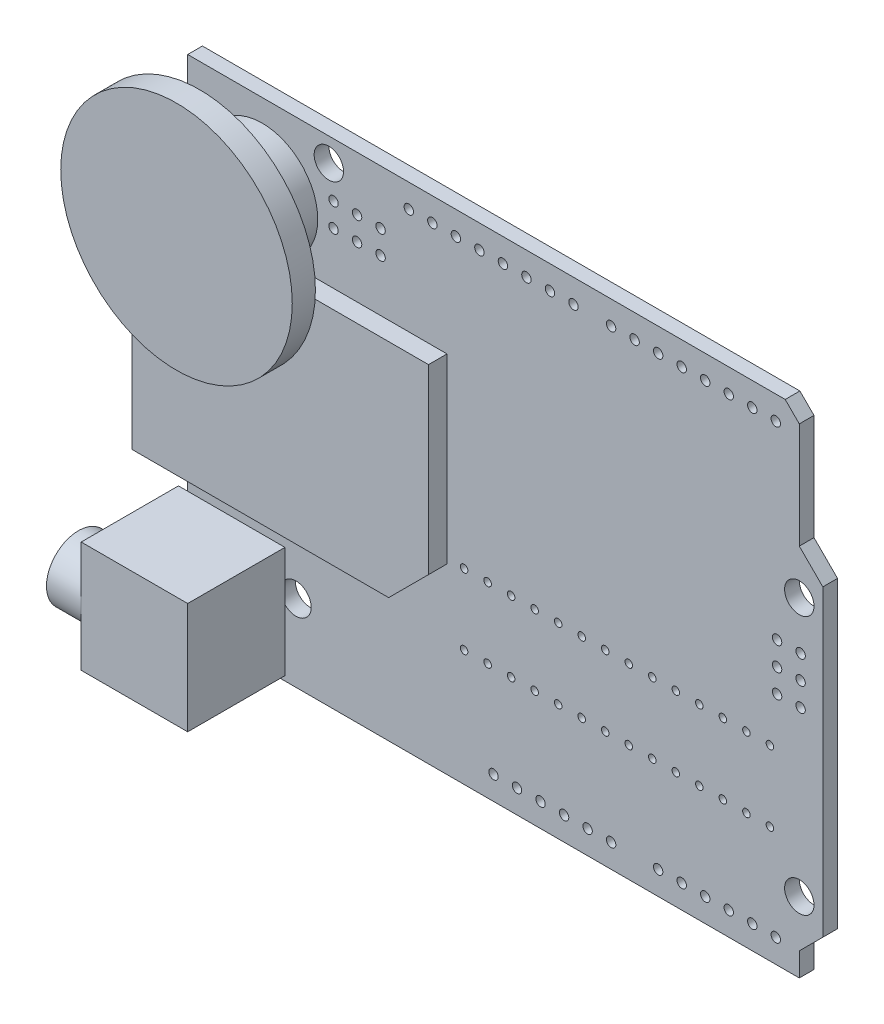
SolidWorks part; units mm, degrees
ref_plane "Front" through (0, 0, 0) normal (0, 0, 1) x (1, 0, 0)
ref_plane "Top" through (0, 0, 0) normal (0, 1, 0) x (1, 0, 0)
ref_plane "Right" through (0, 0, 0) normal (1, 0, 0) x (0, 0, -1)
sketch "Sketch1" plane through (0, 0, 0) normal (0, 0, 1) x (1, 0, 0)
  line L0 (-34.2899, 0) -> (34.2899, 0) construction
  line L1 (0, 0) -> (0, 7.605) construction
  line L2 (31.7499, 13.716) -> (31.7499, 25.146) construction
  line L3 (-34.2899, -26.67) -> (-34.2899, 26.67) construction
  line L4 (-34.2899, -26.67) -> (31.7499, -26.67) construction
  line L5 (31.7499, -26.67) -> (31.7499, -24.13) construction
  line L6 (31.7499, -24.13) -> (34.2899, -21.59) construction
  line L7 (34.2899, -21.59) -> (34.2899, 11.176) construction
  line L8 (31.7499, 13.716) -> (34.2899, 11.176) construction
  line L9 (30.2259, 26.67) -> (31.7499, 25.146) construction
  line L10 (-34.2899, 26.67) -> (30.2259, 26.67) construction
  arc A0 (-21.12, -24.13) -> (-19.5201, -24.13) centre (-20.3201, -24.13) ccw construction
  arc A1 (-19.5201, -24.13) -> (-21.12, -24.13) centre (-20.3201, -24.13) ccw construction
  arc A2 (-19.85, 24.13) -> (-18.2501, 24.13) centre (-19.0501, 24.13) ccw construction
  arc A3 (-18.2501, 24.13) -> (-19.85, 24.13) centre (-19.0501, 24.13) ccw construction
  arc A4 (30.95, -19.05) -> (32.5499, -19.05) centre (31.7499, -19.05) ccw construction
  arc A5 (32.5499, -19.05) -> (30.95, -19.05) centre (31.7499, -19.05) ccw construction
  arc A6 (30.95, 8.89) -> (32.5499, 8.89) centre (31.7499, 8.89) ccw construction
  arc A7 (32.5499, 8.89) -> (30.95, 8.89) centre (31.7499, 8.89) ccw construction
  arc A8 (28.3717, -14.097) -> (28.7781, -14.097) centre (28.5749, -14.097) ccw construction
  arc A9 (28.7781, -14.097) -> (28.3717, -14.097) centre (28.5749, -14.097) ccw construction
  arc A10 (25.8317, -14.097) -> (26.2381, -14.097) centre (26.0349, -14.097) ccw construction
  arc A11 (26.2381, -14.097) -> (25.8317, -14.097) centre (26.0349, -14.097) ccw construction
  arc A12 (23.2917, -14.097) -> (23.6981, -14.097) centre (23.4949, -14.097) ccw construction
  arc A13 (23.6981, -14.097) -> (23.2917, -14.097) centre (23.4949, -14.097) ccw construction
  arc A14 (20.7517, -14.097) -> (21.1581, -14.097) centre (20.9549, -14.097) ccw construction
  arc A15 (21.1581, -14.097) -> (20.7517, -14.097) centre (20.9549, -14.097) ccw construction
  arc A16 (18.2117, -14.097) -> (18.6181, -14.097) centre (18.4149, -14.097) ccw construction
  arc A17 (18.6181, -14.097) -> (18.2117, -14.097) centre (18.4149, -14.097) ccw construction
  arc A18 (15.6717, -14.097) -> (16.0781, -14.097) centre (15.8749, -14.097) ccw construction
  arc A19 (16.0781, -14.097) -> (15.6717, -14.097) centre (15.8749, -14.097) ccw construction
  arc A20 (13.1317, -14.097) -> (13.5381, -14.097) centre (13.3349, -14.097) ccw construction
  arc A21 (13.5381, -14.097) -> (13.1317, -14.097) centre (13.3349, -14.097) ccw construction
  arc A22 (10.5917, -14.097) -> (10.9981, -14.097) centre (10.7949, -14.097) ccw construction
  arc A23 (10.9981, -14.097) -> (10.5917, -14.097) centre (10.7949, -14.097) ccw construction
  arc A24 (8.0517, -14.097) -> (8.4581, -14.097) centre (8.2549, -14.097) ccw construction
  arc A25 (8.4581, -14.097) -> (8.0517, -14.097) centre (8.2549, -14.097) ccw construction
  arc A26 (5.5117, -14.097) -> (5.9181, -14.097) centre (5.7149, -14.097) ccw construction
  arc A27 (5.9181, -14.097) -> (5.5117, -14.097) centre (5.7149, -14.097) ccw construction
  arc A28 (2.9717, -14.097) -> (3.3781, -14.097) centre (3.1749, -14.097) ccw construction
  arc A29 (3.3781, -14.097) -> (2.9717, -14.097) centre (3.1749, -14.097) ccw construction
  arc A30 (0.4317, -14.097) -> (0.8381, -14.097) centre (0.6349, -14.097) ccw construction
  arc A31 (0.8381, -14.097) -> (0.4317, -14.097) centre (0.6349, -14.097) ccw construction
  arc A32 (-2.1083, -14.097) -> (-1.7019, -14.097) centre (-1.9051, -14.097) ccw construction
  arc A33 (-1.7019, -14.097) -> (-2.1083, -14.097) centre (-1.9051, -14.097) ccw construction
  arc A34 (-4.6483, -14.097) -> (-4.2419, -14.097) centre (-4.4451, -14.097) ccw construction
  arc A35 (-4.2419, -14.097) -> (-4.6483, -14.097) centre (-4.4451, -14.097) ccw construction
  arc A36 (-4.6483, -6.477) -> (-4.2419, -6.477) centre (-4.4451, -6.477) ccw construction
  arc A37 (-4.2419, -6.477) -> (-4.6483, -6.477) centre (-4.4451, -6.477) ccw construction
  arc A38 (-2.1083, -6.477) -> (-1.7019, -6.477) centre (-1.9051, -6.477) ccw construction
  arc A39 (-1.7019, -6.477) -> (-2.1083, -6.477) centre (-1.9051, -6.477) ccw construction
  arc A40 (0.4317, -6.477) -> (0.8381, -6.477) centre (0.6349, -6.477) ccw construction
  arc A41 (0.8381, -6.477) -> (0.4317, -6.477) centre (0.6349, -6.477) ccw construction
  arc A42 (2.9717, -6.477) -> (3.3781, -6.477) centre (3.1749, -6.477) ccw construction
  arc A43 (3.3781, -6.477) -> (2.9717, -6.477) centre (3.1749, -6.477) ccw construction
  arc A44 (5.5117, -6.477) -> (5.9181, -6.477) centre (5.7149, -6.477) ccw construction
  arc A45 (5.9181, -6.477) -> (5.5117, -6.477) centre (5.7149, -6.477) ccw construction
  arc A46 (8.0517, -6.477) -> (8.4581, -6.477) centre (8.2549, -6.477) ccw construction
  arc A47 (8.4581, -6.477) -> (8.0517, -6.477) centre (8.2549, -6.477) ccw construction
  arc A48 (10.5917, -6.477) -> (10.9981, -6.477) centre (10.7949, -6.477) ccw construction
  arc A49 (10.9981, -6.477) -> (10.5917, -6.477) centre (10.7949, -6.477) ccw construction
  arc A50 (13.1317, -6.477) -> (13.5381, -6.477) centre (13.3349, -6.477) ccw construction
  arc A51 (13.5381, -6.477) -> (13.1317, -6.477) centre (13.3349, -6.477) ccw construction
  arc A52 (15.6717, -6.477) -> (16.0781, -6.477) centre (15.8749, -6.477) ccw construction
  arc A53 (16.0781, -6.477) -> (15.6717, -6.477) centre (15.8749, -6.477) ccw construction
  arc A54 (18.2117, -6.477) -> (18.6181, -6.477) centre (18.4149, -6.477) ccw construction
  arc A55 (18.6181, -6.477) -> (18.2117, -6.477) centre (18.4149, -6.477) ccw construction
  arc A56 (20.7517, -6.477) -> (21.1581, -6.477) centre (20.9549, -6.477) ccw construction
  arc A57 (21.1581, -6.477) -> (20.7517, -6.477) centre (20.9549, -6.477) ccw construction
  arc A58 (23.2917, -6.477) -> (23.6981, -6.477) centre (23.4949, -6.477) ccw construction
  arc A59 (23.6981, -6.477) -> (23.2917, -6.477) centre (23.4949, -6.477) ccw construction
  arc A60 (25.8317, -6.477) -> (26.2381, -6.477) centre (26.0349, -6.477) ccw construction
  arc A61 (26.2381, -6.477) -> (25.8317, -6.477) centre (26.0349, -6.477) ccw construction
  arc A62 (28.3717, -6.477) -> (28.7781, -6.477) centre (28.5749, -6.477) ccw construction
  arc A63 (28.7781, -6.477) -> (28.3717, -6.477) centre (28.5749, -6.477) ccw construction
  arc A64 (-31.0299, 5.43) -> (-29.93, 5.43) centre (-30.4799, 5.43) ccw construction
  arc A65 (-29.93, 5.43) -> (-31.0299, 5.43) centre (-30.4799, 5.43) ccw construction
  arc A66 (-31.0299, 17.43) -> (-29.93, 17.43) centre (-30.4799, 17.43) ccw construction
  arc A67 (-29.93, 17.43) -> (-31.0299, 17.43) centre (-30.4799, 17.43) ccw construction
  arc A68 (-28.0074, 10.1801) -> (-27.5324, 10.1801) centre (-27.7699, 10.1801) ccw construction
  arc A69 (-27.5324, 10.1801) -> (-28.0074, 10.1801) centre (-27.7699, 10.1801) ccw construction
  arc A70 (-28.0074, 12.6799) -> (-27.5324, 12.6799) centre (-27.7699, 12.6799) ccw construction
  arc A71 (-27.5324, 12.6799) -> (-28.0074, 12.6799) centre (-27.7699, 12.6799) ccw construction
  arc A72 (-26.0075, 12.6799) -> (-25.5325, 12.6799) centre (-25.77, 12.6799) ccw construction
  arc A73 (-25.5325, 12.6799) -> (-26.0075, 12.6799) centre (-25.77, 12.6799) ccw construction
  arc A74 (-26.0075, 10.1801) -> (-25.5325, 10.1801) centre (-25.77, 10.1801) ccw construction
  arc A75 (-25.5325, 10.1801) -> (-26.0075, 10.1801) centre (-25.77, 10.1801) ccw construction
  arc A76 (-29.4258, -18.3642) -> (-27.7748, -18.3642) centre (-28.6003, -18.3642) ccw construction
  arc A77 (-27.7748, -18.3642) -> (-29.4258, -18.3642) centre (-28.6003, -18.3642) ccw construction
  arc A78 (-23.4316, -18.3642) -> (-21.7806, -18.3642) centre (-22.6061, -18.3642) ccw construction
  arc A79 (-21.7806, -18.3642) -> (-23.4316, -18.3642) centre (-22.6061, -18.3642) ccw construction
  arc A80 (-26.4286, -23.368) -> (-24.7776, -23.368) centre (-25.6031, -23.368) ccw construction
  arc A81 (-24.7776, -23.368) -> (-26.4286, -23.368) centre (-25.6031, -23.368) ccw construction
  arc A82 (8.7375, -2.54) -> (9.0423, -2.54) centre (8.8899, -2.54) ccw construction
  arc A83 (9.0423, -2.54) -> (8.7375, -2.54) centre (8.8899, -2.54) ccw construction
  arc A84 (3.6575, -2.54) -> (3.9623, -2.54) centre (3.8099, -2.54) ccw construction
  arc A85 (3.9623, -2.54) -> (3.6575, -2.54) centre (3.8099, -2.54) ccw construction
  arc A86 (-20.4725, 3.81) -> (-20.1677, 3.81) centre (-20.3201, 3.81) ccw construction
  arc A87 (-20.1677, 3.81) -> (-20.4725, 3.81) centre (-20.3201, 3.81) ccw construction
  arc A88 (-15.3925, 3.81) -> (-15.0877, 3.81) centre (-15.2401, 3.81) ccw construction
  arc A89 (-15.0877, 3.81) -> (-15.3925, 3.81) centre (-15.2401, 3.81) ccw construction
  arc A90 (11.1759, -24.13) -> (11.6839, -24.13) centre (11.4299, -24.13) ccw construction
  arc A91 (11.6839, -24.13) -> (11.1759, -24.13) centre (11.4299, -24.13) ccw construction
  arc A92 (8.6359, -24.13) -> (9.1439, -24.13) centre (8.8899, -24.13) ccw construction
  arc A93 (9.1439, -24.13) -> (8.6359, -24.13) centre (8.8899, -24.13) ccw construction
  arc A94 (6.0959, -24.13) -> (6.6039, -24.13) centre (6.3499, -24.13) ccw construction
  arc A95 (6.6039, -24.13) -> (6.0959, -24.13) centre (6.3499, -24.13) ccw construction
  arc A96 (3.5559, -24.13) -> (4.0639, -24.13) centre (3.8099, -24.13) ccw construction
  arc A97 (4.0639, -24.13) -> (3.5559, -24.13) centre (3.8099, -24.13) ccw construction
  arc A98 (1.0159, -24.13) -> (1.5239, -24.13) centre (1.2699, -24.13) ccw construction
  arc A99 (1.5239, -24.13) -> (1.0159, -24.13) centre (1.2699, -24.13) ccw construction
  arc A100 (-1.5241, -24.13) -> (-1.0161, -24.13) centre (-1.2701, -24.13) ccw construction
  arc A101 (-1.0161, -24.13) -> (-1.5241, -24.13) centre (-1.2701, -24.13) ccw construction
  arc A102 (11.1759, 24.13) -> (11.6839, 24.13) centre (11.4299, 24.13) ccw construction
  arc A103 (11.6839, 24.13) -> (11.1759, 24.13) centre (11.4299, 24.13) ccw construction
  arc A104 (13.7159, 24.13) -> (14.2239, 24.13) centre (13.9699, 24.13) ccw construction
  arc A105 (14.2239, 24.13) -> (13.7159, 24.13) centre (13.9699, 24.13) ccw construction
  arc A106 (16.2559, 24.13) -> (16.7639, 24.13) centre (16.5099, 24.13) ccw construction
  arc A107 (16.7639, 24.13) -> (16.2559, 24.13) centre (16.5099, 24.13) ccw construction
  arc A108 (18.7959, 24.13) -> (19.3039, 24.13) centre (19.0499, 24.13) ccw construction
  arc A109 (19.3039, 24.13) -> (18.7959, 24.13) centre (19.0499, 24.13) ccw construction
  arc A110 (21.3359, 24.13) -> (21.8439, 24.13) centre (21.5899, 24.13) ccw construction
  arc A111 (21.8439, 24.13) -> (21.3359, 24.13) centre (21.5899, 24.13) ccw construction
  arc A112 (23.8759, 24.13) -> (24.3839, 24.13) centre (24.1299, 24.13) ccw construction
  arc A113 (24.3839, 24.13) -> (23.8759, 24.13) centre (24.1299, 24.13) ccw construction
  arc A114 (26.4159, 24.13) -> (26.9239, 24.13) centre (26.6699, 24.13) ccw construction
  arc A115 (26.9239, 24.13) -> (26.4159, 24.13) centre (26.6699, 24.13) ccw construction
  arc A116 (28.9559, 24.13) -> (29.4639, 24.13) centre (29.2099, 24.13) ccw construction
  arc A117 (29.4639, 24.13) -> (28.9559, 24.13) centre (29.2099, 24.13) ccw construction
  arc A118 (-10.6681, 24.13) -> (-10.1601, 24.13) centre (-10.4141, 24.13) ccw construction
  arc A119 (-10.1601, 24.13) -> (-10.6681, 24.13) centre (-10.4141, 24.13) ccw construction
  arc A120 (-8.1281, 24.13) -> (-7.6201, 24.13) centre (-7.8741, 24.13) ccw construction
  arc A121 (-7.6201, 24.13) -> (-8.1281, 24.13) centre (-7.8741, 24.13) ccw construction
  arc A122 (-5.5881, 24.13) -> (-5.0801, 24.13) centre (-5.3341, 24.13) ccw construction
  arc A123 (-5.0801, 24.13) -> (-5.5881, 24.13) centre (-5.3341, 24.13) ccw construction
  arc A124 (-3.0481, 24.13) -> (-2.5401, 24.13) centre (-2.7941, 24.13) ccw construction
  arc A125 (-2.5401, 24.13) -> (-3.0481, 24.13) centre (-2.7941, 24.13) ccw construction
  arc A126 (-0.5081, 24.13) -> (-0.0001, 24.13) centre (-0.2541, 24.13) ccw construction
  arc A127 (-0.0001, 24.13) -> (-0.5081, 24.13) centre (-0.2541, 24.13) ccw construction
  arc A128 (2.0319, 24.13) -> (2.5399, 24.13) centre (2.2859, 24.13) ccw construction
  arc A129 (2.5399, 24.13) -> (2.0319, 24.13) centre (2.2859, 24.13) ccw construction
  arc A130 (4.5719, 24.13) -> (5.0799, 24.13) centre (4.8259, 24.13) ccw construction
  arc A131 (5.0799, 24.13) -> (4.5719, 24.13) centre (4.8259, 24.13) ccw construction
  arc A132 (7.1119, 24.13) -> (7.6199, 24.13) centre (7.3659, 24.13) ccw construction
  arc A133 (7.6199, 24.13) -> (7.1119, 24.13) centre (7.3659, 24.13) ccw construction
  arc A134 (-18.7961, 18.288) -> (-18.2881, 18.288) centre (-18.5421, 18.288) ccw construction
  arc A135 (-18.2881, 18.288) -> (-18.7961, 18.288) centre (-18.5421, 18.288) ccw construction
  arc A136 (-18.7961, 20.828) -> (-18.2881, 20.828) centre (-18.5421, 20.828) ccw construction
  arc A137 (-18.2881, 20.828) -> (-18.7961, 20.828) centre (-18.5421, 20.828) ccw construction
  arc A138 (-16.2561, 18.288) -> (-15.7481, 18.288) centre (-16.0021, 18.288) ccw construction
  arc A139 (-15.7481, 18.288) -> (-16.2561, 18.288) centre (-16.0021, 18.288) ccw construction
  arc A140 (-16.2561, 20.828) -> (-15.7481, 20.828) centre (-16.0021, 20.828) ccw construction
  arc A141 (-15.7481, 20.828) -> (-16.2561, 20.828) centre (-16.0021, 20.828) ccw construction
  arc A142 (-13.7161, 18.288) -> (-13.2081, 18.288) centre (-13.4621, 18.288) ccw construction
  arc A143 (-13.2081, 18.288) -> (-13.7161, 18.288) centre (-13.4621, 18.288) ccw construction
  arc A144 (-13.7161, 20.828) -> (-13.2081, 20.828) centre (-13.4621, 20.828) ccw construction
  arc A145 (-13.2081, 20.828) -> (-13.7161, 20.828) centre (-13.4621, 20.828) ccw construction
  arc A146 (31.6362, -1.32) -> (32.1442, -1.32) centre (31.8902, -1.32) ccw construction
  arc A147 (32.1442, -1.32) -> (31.6362, -1.32) centre (31.8902, -1.32) ccw construction
  arc A148 (29.0962, -1.32) -> (29.6042, -1.32) centre (29.3502, -1.32) ccw construction
  arc A149 (29.6042, -1.32) -> (29.0962, -1.32) centre (29.3502, -1.32) ccw construction
  arc A150 (31.6362, 1.22) -> (32.1442, 1.22) centre (31.8902, 1.22) ccw construction
  arc A151 (32.1442, 1.22) -> (31.6362, 1.22) centre (31.8902, 1.22) ccw construction
  arc A152 (29.0962, 1.22) -> (29.6042, 1.22) centre (29.3502, 1.22) ccw construction
  arc A153 (29.6042, 1.22) -> (29.0962, 1.22) centre (29.3502, 1.22) ccw construction
  arc A154 (31.6362, 3.76) -> (32.1442, 3.76) centre (31.8902, 3.76) ccw construction
  arc A155 (32.1442, 3.76) -> (31.6362, 3.76) centre (31.8902, 3.76) ccw construction
  arc A156 (29.0962, 3.76) -> (29.6042, 3.76) centre (29.3502, 3.76) ccw construction
  arc A157 (29.6042, 3.76) -> (29.0962, 3.76) centre (29.3502, 3.76) ccw construction
  arc A158 (28.9559, -24.13) -> (29.4639, -24.13) centre (29.2099, -24.13) ccw construction
  arc A159 (29.4639, -24.13) -> (28.9559, -24.13) centre (29.2099, -24.13) ccw construction
  arc A160 (26.4159, -24.13) -> (26.9239, -24.13) centre (26.6699, -24.13) ccw construction
  arc A161 (26.9239, -24.13) -> (26.4159, -24.13) centre (26.6699, -24.13) ccw construction
  arc A162 (23.8759, -24.13) -> (24.3839, -24.13) centre (24.1299, -24.13) ccw construction
  arc A163 (24.3839, -24.13) -> (23.8759, -24.13) centre (24.1299, -24.13) ccw construction
  arc A164 (21.3359, -24.13) -> (21.8439, -24.13) centre (21.5899, -24.13) ccw construction
  arc A165 (21.8439, -24.13) -> (21.3359, -24.13) centre (21.5899, -24.13) ccw construction
  arc A166 (18.7959, -24.13) -> (19.3039, -24.13) centre (19.0499, -24.13) ccw construction
  arc A167 (19.3039, -24.13) -> (18.7959, -24.13) centre (19.0499, -24.13) ccw construction
  arc A168 (16.2559, -24.13) -> (16.7639, -24.13) centre (16.5099, -24.13) ccw construction
  arc A169 (16.7639, -24.13) -> (16.2559, -24.13) centre (16.5099, -24.13) ccw construction
sketch "Sketch2" plane through (0, 0, 0) normal (0, 0, 1) x (1, 0, 0)
  line L0 (-34.2899, 26.67) -> (30.2259, 26.67) construction
  line L1 (-34.2899, -26.67) -> (-34.2899, 26.67) construction
  line L2 (-34.2899, -26.67) -> (31.7499, -26.67) construction
  line L3 (31.7499, -26.67) -> (31.7499, -24.13) construction
  line L4 (31.7499, -24.13) -> (34.2899, -21.59) construction
  line L5 (34.2899, -21.59) -> (34.2899, 11.176) construction
  line L6 (31.7499, 13.716) -> (34.2899, 11.176) construction
  line L7 (31.7499, 13.716) -> (31.7499, 25.146) construction
  line L8 (30.2259, 26.67) -> (31.7499, 25.146) construction
  line L9 (-34.2899, 26.67) -> (30.2259, 26.67)
  line L10 (-34.2899, -26.67) -> (-34.2899, 26.67)
  line L11 (-34.2899, -26.67) -> (31.7499, -26.67)
  line L12 (31.7499, -26.67) -> (31.7499, -24.13)
  line L13 (31.7499, -24.13) -> (34.2899, -21.59)
  line L14 (34.2899, -21.59) -> (34.2899, 11.176)
  line L15 (31.7499, 13.716) -> (34.2899, 11.176)
  line L16 (31.7499, 13.716) -> (31.7499, 25.146)
  line L17 (30.2259, 26.67) -> (31.7499, 25.146)
extrude "Boss-Extrude1" add sketch "Sketch2" against normal blind 1.5875
sketch "Sketch3" plane through (0, 0, 0) normal (0, 0, 1) x (1, 0, 0)
  circle A0 centre (-30.4799, 17.43) radius 1.1049
  circle A1 centre (-30.4799, 5.43) radius 1.1049
  circle A2 centre (-28.6003, -18.3642) radius 1.651
  circle A3 centre (-25.6031, -23.368) radius 1.651
  circle A4 centre (-22.6061, -18.3642) radius 1.651
  circle A5 centre (31.7499, -19.05) radius 1.5875
  circle A6 centre (31.7499, 8.89) radius 1.5875
  circle A7 centre (-19.0501, 24.13) radius 1.5875
  circle A8 centre (-25.77, 12.6799) radius 0.4826
  circle A9 centre (-27.7699, 12.6799) radius 0.4826
  circle A10 centre (-27.7699, 10.1801) radius 0.4826
  circle A11 centre (-25.77, 10.1801) radius 0.4826
  dimension "D1" = 3.175
  dimension "D2" = 3.175
  dimension "D3" = 3.175
  dimension "D4" = 3.302
  dimension "D5" = 3.302
  dimension "D6" = 3.302
  dimension "D7" = 2.2098
  dimension "D8" = 2.2098
  dimension "D9" = 0.9652
  dimension "D10" = 0.9652
  dimension "D11" = 0.9652
  dimension "D12" = 0.9652
extrude "Cut-Extrude1" cut sketch "Sketch3" against normal through all
sketch "Sketch4" plane through (0, 0, 0) normal (0, 0, 1) x (1, 0, 0)
  circle A0 centre (29.2099, 24.13) radius 0.508
  circle A1 centre (26.6699, 24.13) radius 0.508
  circle A2 centre (24.1299, 24.13) radius 0.508
  circle A3 centre (21.5899, 24.13) radius 0.508
  circle A4 centre (19.0499, 24.13) radius 0.508
  circle A5 centre (16.5099, 24.13) radius 0.508
  circle A6 centre (13.9699, 24.13) radius 0.508
  circle A7 centre (11.4299, 24.13) radius 0.508
  circle A8 centre (7.3659, 24.13) radius 0.508
  circle A9 centre (4.8259, 24.13) radius 0.508
  circle A10 centre (2.2859, 24.13) radius 0.508
  circle A11 centre (-0.2541, 24.13) radius 0.508
  circle A12 centre (-2.7941, 24.13) radius 0.508
  circle A13 centre (-5.3341, 24.13) radius 0.508
  circle A14 centre (-7.8741, 24.13) radius 0.508
  circle A15 centre (-10.4141, 24.13) radius 0.508
  circle A16 centre (28.5749, -6.477) radius 0.4064
  circle A17 centre (26.0349, -6.477) radius 0.4064
  circle A18 centre (23.4949, -6.477) radius 0.4064
  circle A19 centre (20.9549, -6.477) radius 0.4064
  circle A20 centre (18.4149, -6.477) radius 0.4064
  circle A21 centre (15.8749, -6.477) radius 0.4064
  circle A22 centre (13.3349, -6.477) radius 0.4064
  circle A23 centre (10.7949, -6.477) radius 0.4064
  circle A24 centre (8.2549, -6.477) radius 0.4064
  circle A25 centre (5.7149, -6.477) radius 0.4064
  circle A26 centre (3.1749, -6.477) radius 0.4064
  circle A27 centre (0.6349, -6.477) radius 0.4064
  circle A28 centre (-1.9051, -6.477) radius 0.4064
  circle A29 centre (-4.4451, -6.477) radius 0.4064
  circle A30 centre (28.5749, -14.097) radius 0.4064
  circle A31 centre (26.0349, -14.097) radius 0.4064
  circle A32 centre (23.4949, -14.097) radius 0.4064
  circle A33 centre (20.9549, -14.097) radius 0.4064
  circle A34 centre (18.4149, -14.097) radius 0.4064
  circle A35 centre (15.8749, -14.097) radius 0.4064
  circle A36 centre (13.3349, -14.097) radius 0.4064
  circle A37 centre (10.7949, -14.097) radius 0.4064
  circle A38 centre (8.2549, -14.097) radius 0.4064
  circle A39 centre (5.7149, -14.097) radius 0.4064
  circle A40 centre (3.1749, -14.097) radius 0.4064
  circle A41 centre (0.6349, -14.097) radius 0.4064
  circle A42 centre (-1.9051, -14.097) radius 0.4064
  circle A43 centre (-4.4451, -14.097) radius 0.4064
  circle A44 centre (29.2099, -24.13) radius 0.508
  circle A45 centre (11.4299, -24.13) radius 0.508
  circle A46 centre (26.6699, -24.13) radius 0.508
  circle A47 centre (8.8899, -24.13) radius 0.508
  circle A48 centre (24.1299, -24.13) radius 0.508
  circle A49 centre (6.3499, -24.13) radius 0.508
  circle A50 centre (21.5899, -24.13) radius 0.508
  circle A51 centre (3.8099, -24.13) radius 0.508
  circle A52 centre (19.0499, -24.13) radius 0.508
  circle A53 centre (1.2699, -24.13) radius 0.508
  circle A54 centre (16.5099, -24.13) radius 0.508
  circle A55 centre (-1.2701, -24.13) radius 0.508
  circle A56 centre (-13.4621, 20.828) radius 0.508
  circle A57 centre (-13.4621, 18.288) radius 0.508
  circle A58 centre (-16.0021, 18.288) radius 0.508
  circle A59 centre (-16.0021, 20.828) radius 0.508
  circle A60 centre (-18.5421, 18.288) radius 0.508
  circle A61 centre (-18.5421, 20.828) radius 0.508
  circle A62 centre (31.8902, -1.32) radius 0.508
  circle A63 centre (29.3502, -1.32) radius 0.508
  circle A64 centre (29.3502, 1.22) radius 0.508
  circle A65 centre (31.8902, 1.22) radius 0.508
  circle A66 centre (29.3502, 3.76) radius 0.508
  circle A67 centre (31.8902, 3.76) radius 0.508
  dimension "D1" = 1.016
  dimension "D3" = 1.016
  dimension "D5" = 0.8128
  dimension "D7" = 0.8128
  dimension "D9" = 1.016
  dimension "D10" = 1.016
  dimension "D12" = 1.016
  dimension "D13" = 1.016
  dimension "D15" = 1.016
  dimension "D16" = 1.016
  dimension "D2" = 8
  dimension "D4" = 8
  dimension "D6" = 14
  dimension "D8" = 14
  dimension "D11" = 6
  dimension "D14" = 3
  dimension "D17" = 3
extrude "Cut-Extrude2" cut sketch "Sketch4" against normal through all
sketch "Sketch5" plane through (0, 0, 0) normal (0, 0, 1) x (1, 0, 0)
  line L0 (-34.2899, -26.67) -> (31.7499, -26.67) construction
  line L1 (-35.2899, -26.17) -> (-23.7899, -26.17)
  line L2 (-35.2899, -26.17) -> (-35.2899, -14.17)
  line L3 (-35.2899, -14.17) -> (-23.7899, -14.17)
  line L4 (-23.7899, -26.17) -> (-23.7899, -14.17)
  line L5 (-34.2899, -26.67) -> (-34.2899, 26.67) construction
  dimension "D1" = 11.5
  dimension "D2" = 12
  dimension "D3" = 0.5
  dimension "D4" = 1
extrude "headphone_jack" add sketch "Sketch5" along normal blind 10.5 separate body
sketch "Sketch6" plane through (-35.2899, 0, 0) normal (-1, 0, 0) x (0, 0, 1)
  line L0 (7.04, -20.17) -> (10.5, -20.17) construction
  line L1 (10.5, -14.17) -> (10.5, -26.17) construction
  circle A0 centre (7.04, -20.17) radius 3.46
  circle A1 centre (7.04, -20.17) radius 1.75
  dimension "D1" = 6.92
  dimension "D2" = 3.5
extrude "headphone_port" add sketch "Sketch6" along normal blind 3.75
sketch "Sketch7" plane through (0, 0, 0) normal (0, 0, 1) x (1, 0, 0)
  circle A0 centre (-26.2496, 18.2791) radius 6
  dimension "D1" = 12
extrude "knob_base" add sketch "Sketch7" along normal blind 6.75 separate body
sketch "Sketch8" plane through (0, 0, 6.75) normal (0, 0, 1) x (1, 0, 0)
  circle A0 centre (-26.2496, 18.2791) radius 12.5
  circle A1 centre (-26.2496, 18.2791) radius 6 construction
  dimension "D1" = 25
extrude "volume_knob" add sketch "Sketch8" along normal blind 2.5
sketch "Sketch9" plane through (0, 0, 0) normal (0, 0, 1) x (1, 0, 0)
  line L0 (-6.2899, -6.97) -> (-10.5899, -11.27)
  line L1 (-38.2899, 12.67) -> (-6.2899, 12.67)
  line L2 (-38.2899, 12.67) -> (-38.2899, -11.27)
  line L3 (-38.2899, -11.27) -> (-10.5899, -11.27)
  line L4 (-6.2899, 12.67) -> (-6.2899, -6.97)
  line L5 (-34.2899, 26.67) -> (30.2259, 26.67) construction
  line L6 (-34.2899, -26.67) -> (-34.2899, 26.67) construction
  point P1 (-6.2899, -11.27)
  dimension "D1" = 23.94
  dimension "D2" = 32
  dimension "D4" = 14
  dimension "D5" = 4
extrude "sd_card" add sketch "Sketch9" along normal blind 2 separate body
